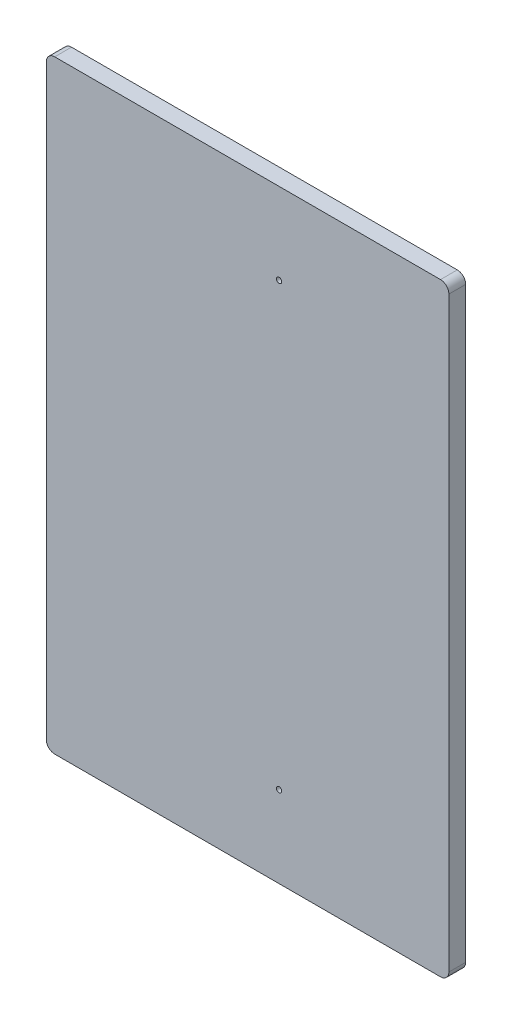
SolidWorks part; units mm, degrees
material "1060 Alloy"
ref_plane "Front Plane" through (0, 0, 0) normal (0, 0, 1) x (1, 0, 0)
ref_plane "Top Plane" through (0, 0, 0) normal (0, 1, 0) x (1, 0, 0)
ref_plane "Right Plane" through (0, 0, 0) normal (1, 0, 0) x (0, 0, -1)
sketch "Sketch2" plane through (0, 0, 0) normal (0, 0, 1) x (1, 0, 0)
  line L0 (-152.4, 0) -> (152.4, 0) construction
  line L1 (152.4, 228.6) -> (-152.4, 228.6)
  line L2 (152.4, 228.6) -> (152.4, -228.6)
  line L3 (152.4, -228.6) -> (-152.4, -228.6)
  line L4 (-152.4, 228.6) -> (-152.4, -228.6)
  dimension "D1" = 304.8
  dimension "D2" = 457.2
extrude "Boss-Extrude1" add sketch "Sketch2" along normal blind 12.7
fillet "Fillet1" radius 6.35 4 edges at (152.4, 228.6, 6.35) (152.4, -228.6, 6.35) (-152.4, -228.6, 6.35) (-152.4, 228.6, 6.35)
hole_wizard "#10-32 Tapped Hole1" positions "Sketch5" profile "Sketch6" tap size "#10-32" standard "Ansi Inch" end condition through all
sketch "Sketch5" plane through (0, 0, 0) normal (0, 0, -1) x (-1, 0, 0)
  point P0 (-23.8125, -167.005)
  point P1 (-23.8125, 167.005)
sketch "Sketch6" plane through (23.8125, -167.005, 0) normal (1, 0, 0) x (0, 1, 0)
  line L0 (0, 0) -> (0, 12.7)
  line L1 (0, 12.7) -> (2.0193, 12.7)
  line L2 (2.0193, 12.7) -> (2.0193, 0)
  line L5 (2.0193, 0) -> (0, 0)
  line L11 (0, -6.35) -> (0, 107.95) construction
  dimension "Thru Tap Drill Dia." = 4.0386
  dimension "Thru Tap Drill Depth" = 12.7
cosmetic thread "Hole Thread1" parameters "D2"=4.826
cosmetic thread "Hole Thread2" parameters "D2"=4.826
